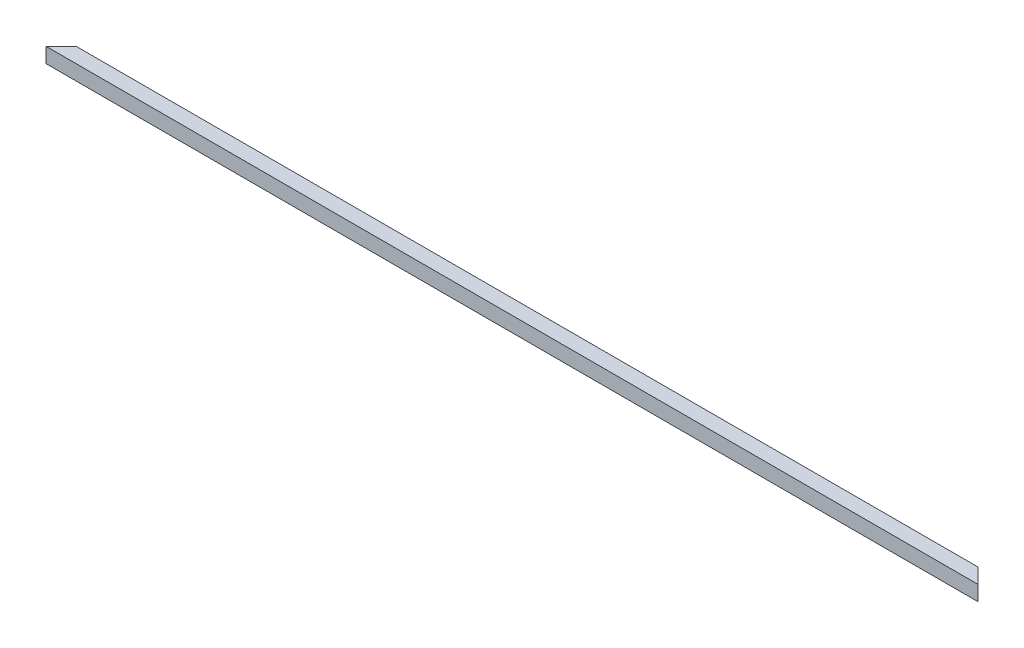
SolidWorks part; units mm, degrees
ref_plane "Front Plane" through (0, 0, 0) normal (0, 0, 1) x (1, 0, 0)
ref_plane "Top Plane" through (0, 0, 0) normal (0, 1, 0) x (1, 0, 0)
ref_plane "Right Plane" through (0, 0, 0) normal (1, 0, 0) x (0, 0, -1)
sketch "Sketch1" plane through (0, 0, 0) normal (1, 0, 0) x (0, 0, -1)
  line L1 (-11.1125, -11.1125) -> (11.1125, -11.1125)
  line L2 (-11.1125, -11.1125) -> (-11.1125, 11.1125)
  line L3 (-11.1125, 11.1125) -> (11.1125, 11.1125)
  line L4 (11.1125, -11.1125) -> (11.1125, 11.1125)
  line L5 (-11.1125, -11.1125) -> (11.1125, 11.1125) construction
  line L6 (-11.1125, 11.1125) -> (11.1125, -11.1125) construction
  line L7 (-12.7, -12.7) -> (12.7, -12.7)
  line L8 (-12.7, -12.7) -> (-12.7, 12.7)
  line L9 (-12.7, 12.7) -> (12.7, 12.7)
  line L10 (12.7, -12.7) -> (12.7, 12.7)
  line L11 (-12.7, -12.7) -> (12.7, 12.7) construction
  line L12 (-12.7, 12.7) -> (12.7, -12.7) construction
  point P0 (0, 0)
  point P6 (0, 0)
  dimension "D1" = 25.4
  dimension "D2" = 1.5875
extrude "Boss-Extrude1" add sketch "Sketch1" along normal blind 1574.8
ref_plane "Plane1" through (787.4, 0, 0) normal (1, 0, 0) x (0, 0, -1)
sketch "Sketch2" plane through (0, 12.7, 0) normal (0, 1, 0) x (1, 0, 0)
  line L0 (0, -12.7) -> (25.4, 12.7)
  line L1 (1574.8, 12.7) -> (0, 12.7) construction
  line L2 (25.4, 12.7) -> (0, 12.7)
  line L3 (0, 12.7) -> (0, -12.7)
extrude "Cut-Extrude1" cut sketch "Sketch2" against normal through all
mirror "Mirror1" about plane through (787.4, 0, 0) normal (1, 0, 0) of "Cut-Extrude1"
